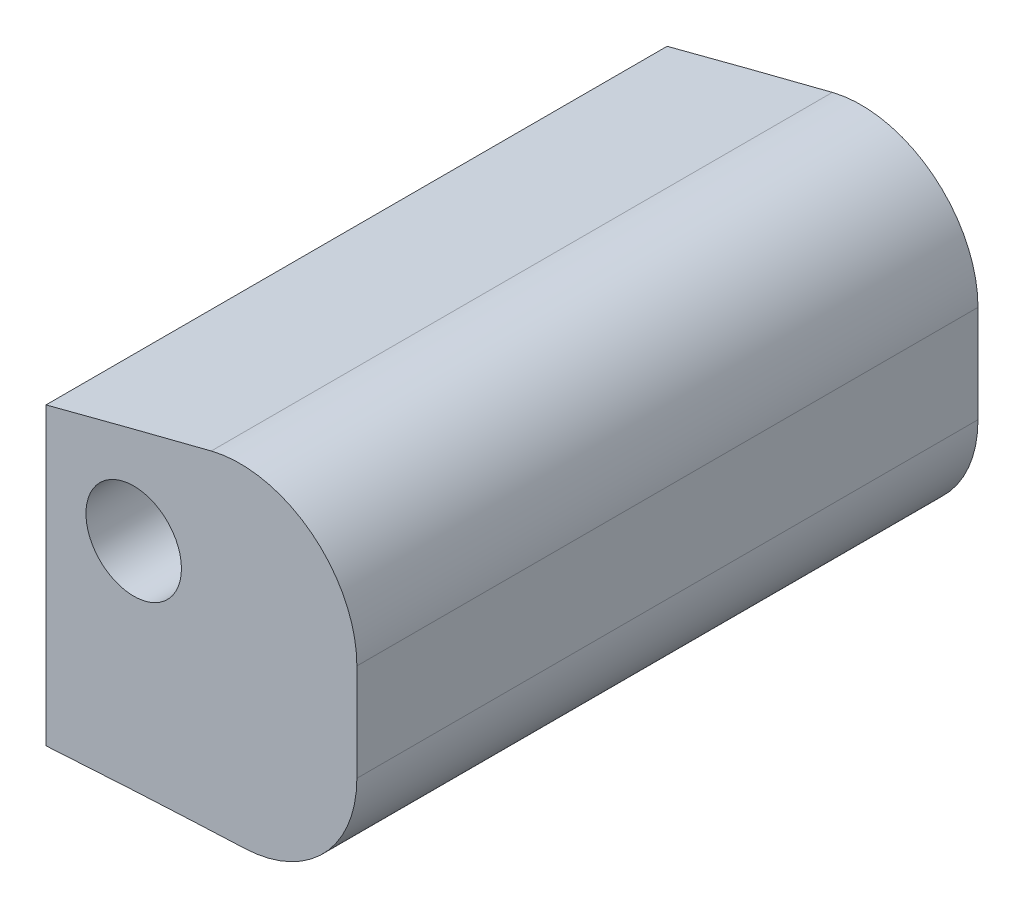
SolidWorks part; units mm, degrees
ref_plane "Front Plane" through (0, 0, 0) normal (0, 0, 1) x (1, 0, 0)
ref_plane "Top Plane" through (0, 0, 0) normal (0, 1, 0) x (1, 0, 0)
ref_plane "Right Plane" through (0, 0, 0) normal (1, 0, 0) x (0, 0, -1)
sketch "Sketch1" plane through (0, 0, 0) normal (0, 0, 1) x (1, 0, 0)
  line L1 (36.0875, 3) -> (36.0875, 7.228)
  circle A3 centre (26.3907, 7.0797) radius 2.075
  arc A4 (31.2216, -2.0755) -> (36.0875, 3) centre (31.0075, 3) ccw
  arc A5 (36.0875, 7.228) -> (29.7604, 12.1525) centre (31.0075, 7.228) ccw
  spline S0 degree 3 poles (-32.0293, -8.1603) (-27.5943, -7.0527) (-20.0884, -6.5835) (-6.7403, -4.761) (4.8697, -4.0726) (18.4945, -2.7427) (26.2047, -2.2872) (31.2216, -2.0755) knots 0 0 0 0 0.144322 0.237948 0.427123 0.512832 0.672025 0.672025 0.672025 0.672025
  spline S1 degree 3 poles (29.7604, 12.1525) (20.1046, 9.7074) (4.1606, 5.3612) (-17.3533, -1.5993) (-25.5736, -4.86) (-35.7724, -8.5491) (-32.0293, -8.1603) knots 0.330745 0.330745 0.330745 0.330745 0.630725 0.824214 0.940085 1 1 1 1
extrude "Boss-Extrude1" add sketch "Sketch1" along normal blind 26.9875
sketch "Sketch2" plane through (0, 0, 26.9875) normal (0, 0, 1) x (1, 0, 0)
  line L1 (22.5807, 14.1313) -> (-63.7836, 14.1313)
  line L2 (22.5807, 14.1313) -> (22.5807, -20.6835)
  line L3 (22.5807, -20.6835) -> (-63.7836, -20.6835)
  line L4 (-63.7836, 14.1313) -> (-63.7836, -20.6835)
  circle A1 centre (26.3907, 7.0797) radius 2.075 construction
  dimension "D1" = 3.81
extrude "Cut-Extrude1" cut sketch "Sketch2" against normal through all
